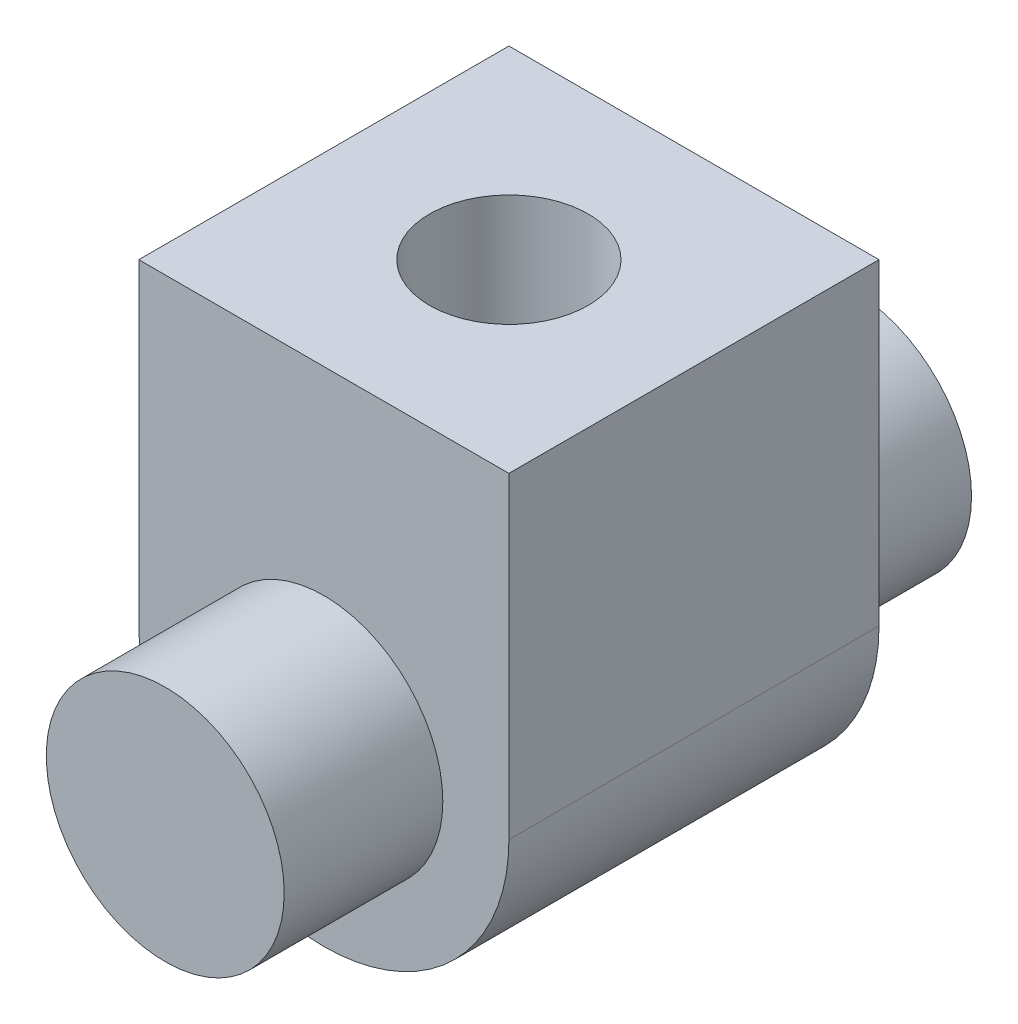
SolidWorks part; units mm, degrees
ref_plane "前基準面" through (0, 0, 0) normal (0, 0, 1) x (1, 0, 0)
ref_plane "上基準面" through (0, 0, 0) normal (0, 1, 0) x (1, 0, 0)
ref_plane "右基準面" through (0, 0, 0) normal (1, 0, 0) x (0, 0, -1)
sketch "草圖1" plane through (0, 0, 0) normal (0, 0, 1) x (1, 0, 0)
  line L0 (-3.5, 0) -> (-3.5, 6)
  line L1 (-3.5, 6) -> (3.5, 6)
  line L2 (3.5, 6) -> (3.5, 0)
  arc A0 (-3.5, 0) -> (3.5, 0) centre (0, 0) ccw
  dimension "D1" = 3.5
  dimension "D2" = 6
extrude "伸長1" add sketch "草圖1" along normal blind 7
sketch "草圖3" plane through (0, 0, 7) normal (0, 0, 1) x (1, 0, 0)
  circle A0 centre (0, 0) radius 2.25
  dimension "D1" = 4.5
extrude "伸長2" add sketch "草圖3" along normal blind 3
sketch "草圖4" plane through (0, 0, 0) normal (0, 0, -1) x (-1, 0, 0)
  circle A0 centre (0, 0) radius 2.25
  dimension "D1" = 4.5
extrude "伸長3" add sketch "草圖4" along normal blind 3
sketch "草圖5" plane through (0, 6, 0) normal (0, 1, 0) x (1, 0, 0)
  line L0 (3.5, 0) -> (-3.5, -7) construction
  circle A0 centre (0, -3.5) radius 1.5
  dimension "D1" = 3
extrude "伸長4" cut sketch "草圖5" against normal blind 5
